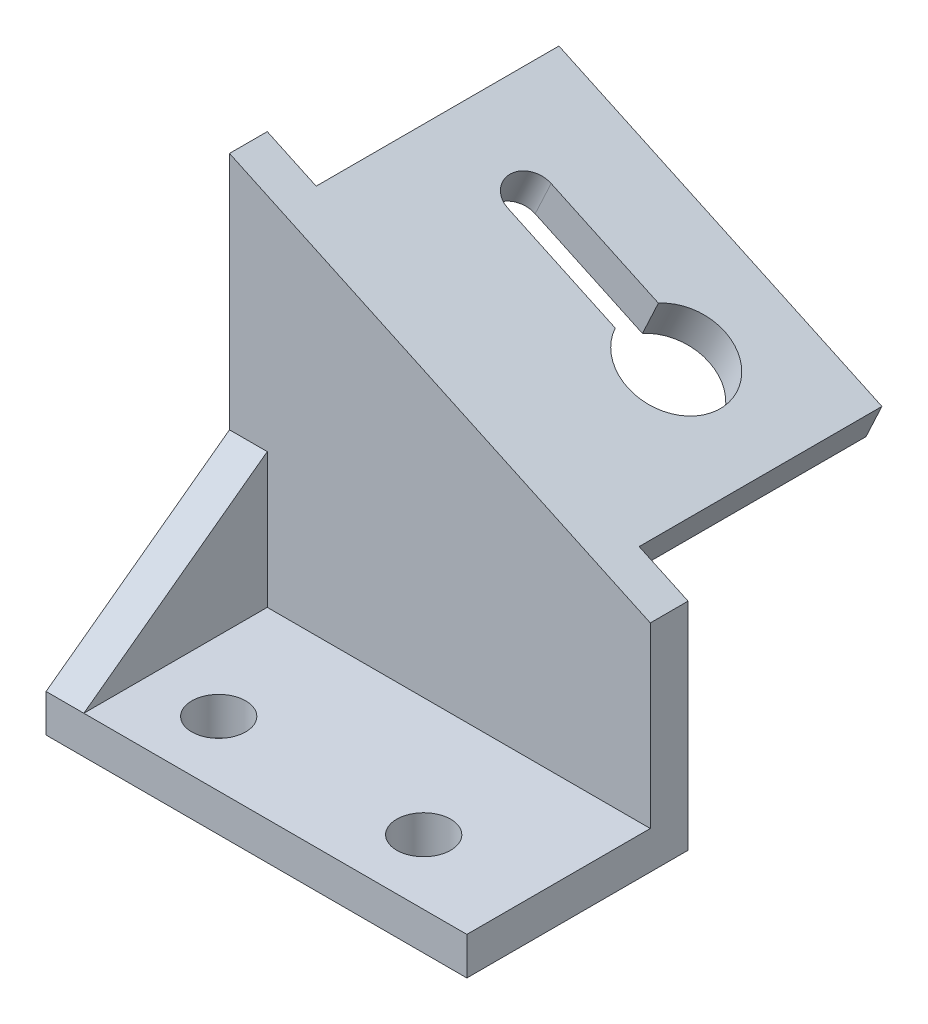
SolidWorks part; units mm, degrees
ref_plane "Front Plane" through (0, 0, 0) normal (0, 0, 1) x (1, 0, 0)
ref_plane "Top Plane" through (0, 0, 0) normal (0, 1, 0) x (1, 0, 0)
ref_plane "Right Plane" through (0, 0, 0) normal (1, 0, 0) x (0, 0, -1)
sketch "Sketch1" plane through (0, 0, 0) normal (0, 1, 0) x (1, 0, 0)
  line L1 (0, 0) -> (78, 0)
  line L2 (0, 0) -> (0, 41)
  line L3 (0, 41) -> (78, 41)
  line L4 (78, 0) -> (78, 41)
  circle A0 centre (20, 12) radius 5
  circle A2 centre (58, 12) radius 5
  dimension "D4" = 20
  dimension "D5" = 10
  dimension "D6" = 10
  dimension "D8" = 12
  dimension "D1" = 41
  dimension "D2" = 78
  dimension "D3" = 12
  dimension "D7" = 20
extrude "Boss-Extrude1" add sketch "Sketch1" along normal blind 7
sketch "Sketch5" plane through (0, 0, 0) normal (0, 0, 1) x (1, 0, 0)
  line L0 (0, 7) -> (0, 76.372)
  line L1 (0, 76.372) -> (78, 40)
  line L2 (78, 40) -> (78, 7)
  line L3 (78, 7) -> (0, 7)
  dimension "D1" = 25
  dimension "D2" = 33
extrude "Boss-Extrude3" add sketch "Sketch5" along normal blind 7 from offset 41 contours L3 L0 L1 L2 offset against normal yes
sketch "Sketch6" plane through (0, 0, 0) normal (1, 0, 0) x (0, 0, -1)
  line L0 (34, 7) -> (34, 32)
  line L1 (34, 40) -> (34, 7) construction
  line L2 (34, 32) -> (0, 7)
  line L3 (0, 7) -> (34, 7)
  dimension "D1" = 25
extrude "Boss-Extrude6" add sketch "Sketch6" along normal blind 7
sketch "Sketch10" plane through (29.2522, 62.7315, 0) normal (0.4226, 0.9063, 0) x (0.9063, -0.4226, 0)
  line L0 (-32.2762, 41) -> (53.7873, 41) construction
  line L1 (-22.2762, 41) -> (43.7873, 41)
  line L2 (-22.2762, 41) -> (-22.2762, 86)
  line L3 (-22.2762, 86) -> (43.7873, 86)
  line L4 (43.7873, 41) -> (43.7873, 86)
  line L5 (53.7873, 34) -> (53.7873, 41) construction
  line L7 (-32.2762, 34) -> (-32.2762, 41) construction
  line L8 (-6.2127, 70) -> (15.725, 70)
  line L9 (-6.2127, 62) -> (15.725, 62)
  arc A0 (15.725, 62) -> (15.725, 70) centre (23.7873, 66) ccw
  arc A1 (-6.2127, 70) -> (-6.2127, 62) centre (-6.2127, 66) ccw
  point P8 (53.7873, 37.5)
  dimension "D6" = 18
  dimension "D7" = 8
  dimension "D1" = 45
  dimension "D2" = 10
  dimension "D3" = 10
  dimension "D4" = 20
  dimension "D5" = 20
  dimension "D8" = 30
extrude "Boss-Extrude7" add sketch "Sketch10" against normal blind 7
